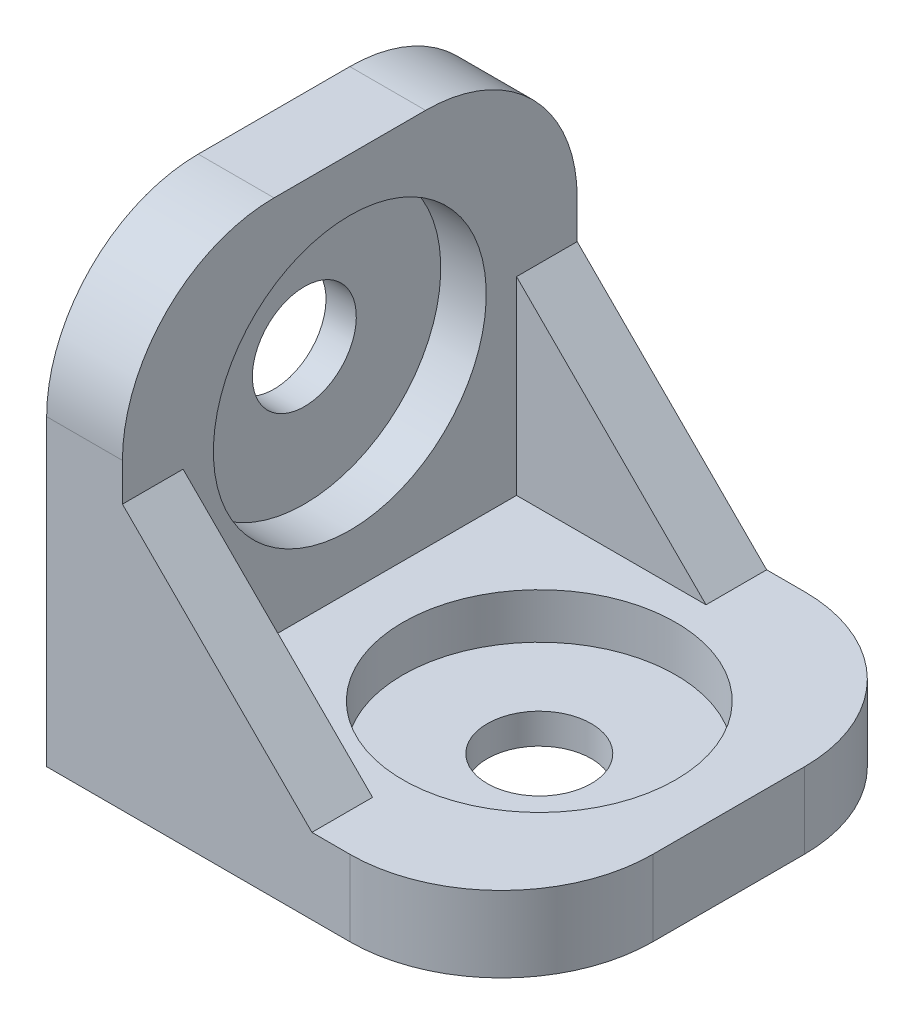
SolidWorks part; units mm, degrees
ref_plane "Front Plane" through (0, 0, 0) normal (0, 0, 1) x (1, 0, 0)
ref_plane "Top Plane" through (0, 0, 0) normal (0, 1, 0) x (1, 0, 0)
ref_plane "Right Plane" through (0, 0, 0) normal (1, 0, 0) x (0, 0, -1)
sketch "Sketch1" plane through (0, 0, 0) normal (0, 0, 1) x (1, 0, 0)
  line L0 (0, 30) -> (0, 0)
  line L1 (0, 0) -> (30, 0)
  line L2 (30, 0) -> (30, 5)
  line L3 (30, 5) -> (5, 5)
  line L4 (5, 5) -> (5, 30)
  line L5 (5, 30) -> (0, 30)
  dimension "D1" = 30
  dimension "D2" = 30
  dimension "D3" = 5
  dimension "D4" = 5
extrude "Boss-Extrude1" add sketch "Sketch1" along normal blind 30
sketch "Sketch2" plane through (5, 0, 0) normal (1, 0, 0) x (0, 0, -1)
  line L0 (-15, 30) -> (-15, 5) construction
  line L1 (-30, 30) -> (0, 30) construction
  line L2 (-30, 5) -> (0, 5) construction
  circle A0 centre (-15, 17.5) radius 3.429
  dimension "D1" = 6.858
extrude "Cut-Extrude1" cut sketch "Sketch2" against normal through all
sketch "Sketch4" plane through (0, 5, 0) normal (0, 1, 0) x (1, 0, 0)
  line L0 (5, -15) -> (30, -15) construction
  line L1 (5, -30) -> (5, 0) construction
  line L2 (30, -30) -> (30, 0) construction
  circle A0 centre (17.5, -15) radius 3.429
  dimension "D1" = 6.858
extrude "Cut-Extrude2" cut sketch "Sketch4" against normal through all and the other way through all
sketch "Sketch7" plane through (0, 5, 0) normal (0, 1, 0) x (1, 0, 0)
  circle A0 centre (17.5, -15) radius 3.429 construction
  circle A1 centre (17.5, -15) radius 3.429 construction
  circle A2 centre (17.5, -15) radius 9
  dimension "D1" = 18
extrude "Cut-Extrude3" cut sketch "Sketch7" against normal blind 3
sketch "Sketch8" plane through (5, 0, 0) normal (1, 0, 0) x (0, 0, -1)
  circle A0 centre (-15, 17.5) radius 9
  dimension "D1" = 18
extrude "Cut-Extrude4" cut sketch "Sketch8" against normal blind 3
sketch "Sketch9" plane through (0, 0, 0) normal (0, 0, -1) x (-1, 0, 0)
  line L0 (-17.5, 5) -> (-5, 17.5)
  line L1 (-30, 5) -> (-5, 5) construction
  line L2 (-5, 5) -> (-5, 30) construction
  line L3 (-17.5, 5) -> (-5, 5)
  line L4 (-5, 5) -> (-5, 17.5)
extrude "Boss-Extrude2" add sketch "Sketch9" against normal blind 4
sketch "Sketch10" plane through (0, 0, 30) normal (0, 0, 1) x (1, 0, 0)
  line L3 (5, 5) -> (17.5, 5)
  line L4 (17.5, 5) -> (5, 17.5)
  line L5 (5, 17.5) -> (5, 5)
  line L6 (5, 5) -> (17.5, 5)
  line L7 (17.5, 5) -> (5, 17.5)
  line L8 (5, 17.5) -> (5, 5)
  dimension "D1" = 0
extrude "Boss-Extrude3" add sketch "Sketch10" against normal blind 4
fillet "Fillet1" radius 10 4 edges at (30, 2.5, 0) (30, 2.5, 30) (2.5, 30, 30) (2.5, 30, 0)
